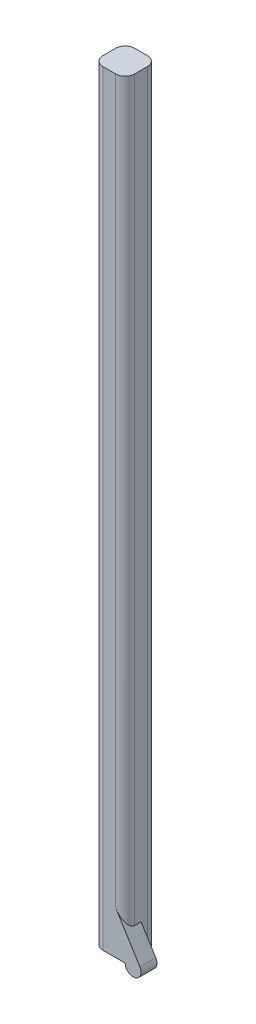
SolidWorks part; units mm, degrees
ref_plane "Front Plane" through (0, 0, 0) normal (0, 0, 1) x (1, 0, 0)
ref_plane "Top Plane" through (0, 0, 0) normal (0, 1, 0) x (1, 0, 0)
ref_plane "Right Plane" through (0, 0, 0) normal (1, 0, 0) x (0, 0, -1)
sketch "Sketch3" plane through (0, 0, 0) normal (0, 1, 0) x (1, 0, 0)
  line L1 (5, -5) -> (-5, -5)
  line L2 (5, -5) -> (5, 5)
  line L3 (5, 5) -> (-5, 5)
  line L4 (-5, -5) -> (-5, 5)
  line L5 (5, -5) -> (-5, 5) construction
  line L6 (5, 5) -> (-5, -5) construction
  point P0 (0, 0)
  dimension "D1" = 10
  dimension "D2" = 10
extrude "Boss-Extrude3" add sketch "Sketch3" along normal blind 241
sketch "Sketch4" plane through (0, 0, 5) normal (0, 0, 1) x (1, 0, 0)
  line L0 (-5, 241) -> (-5, 0) construction
  line L3 (0, 0) -> (0, 30.1571) construction
  line L4 (5, 8.7672) -> (5, 0)
  line L5 (5, 8.7672) -> (9.624, 1.3186)
  arc A1 (9.624, 1.3186) -> (5, 0) centre (7.5, 0) cw
extrude "Boss-Extrude4" add sketch "Sketch4" against normal blind 5
fillet "Fillet1" radius 3 4 edges at (5, 120.5, -5) (-5, 120.5, -5) (5, 124.8836, 5) (-5, 120.5, 5)
